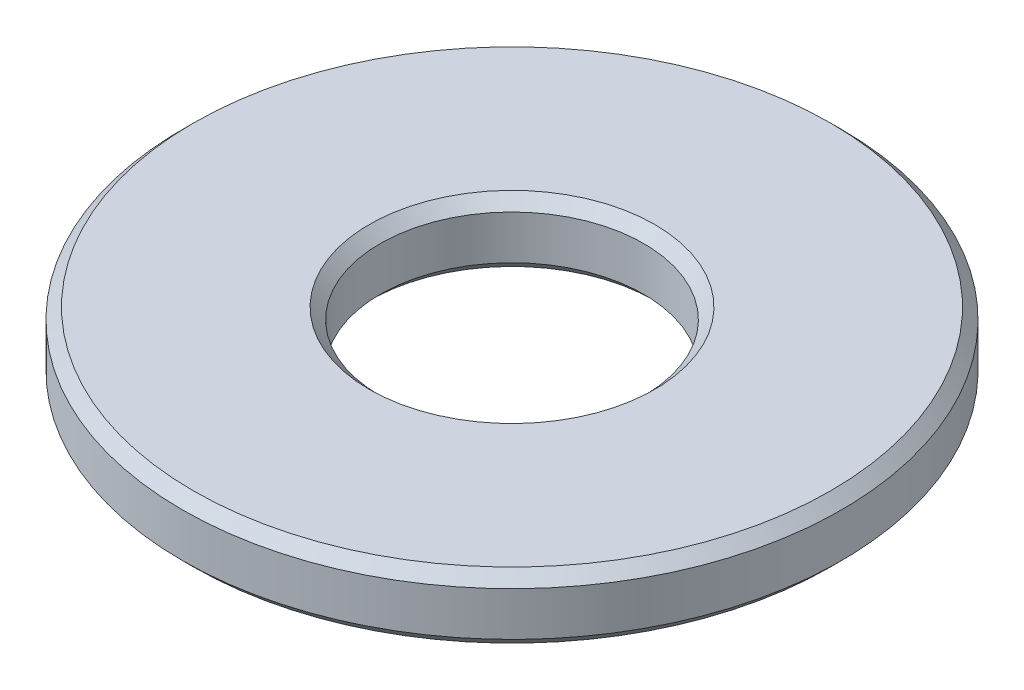
SolidWorks part; units mm, degrees
ref_plane "Спереди" through (0, 0, 0) normal (0, 0, 1) x (1, 0, 0)
ref_plane "Сверху" through (0, 0, 0) normal (0, 1, 0) x (1, 0, 0)
ref_plane "Справа" through (0, 0, 0) normal (1, 0, 0) x (0, 0, -1)
sketch "Эскиз1" plane through (0, 0, 0) normal (0, 1, 0) x (1, 0, 0)
  circle A0 centre (0, 0) radius 6
  circle A1 centre (0, 0) radius 15
  dimension "D1" = 30
  dimension "D2" = 12
extrude "Бобышка-Вытянуть1" add sketch "Эскиз1" along normal blind 3
chamfer "Фаска1" distance 0.5 angle 45 4 edges at (0, 0, 6) (0, 0, 15) (0, 3, 6) (0, 3, 15)
